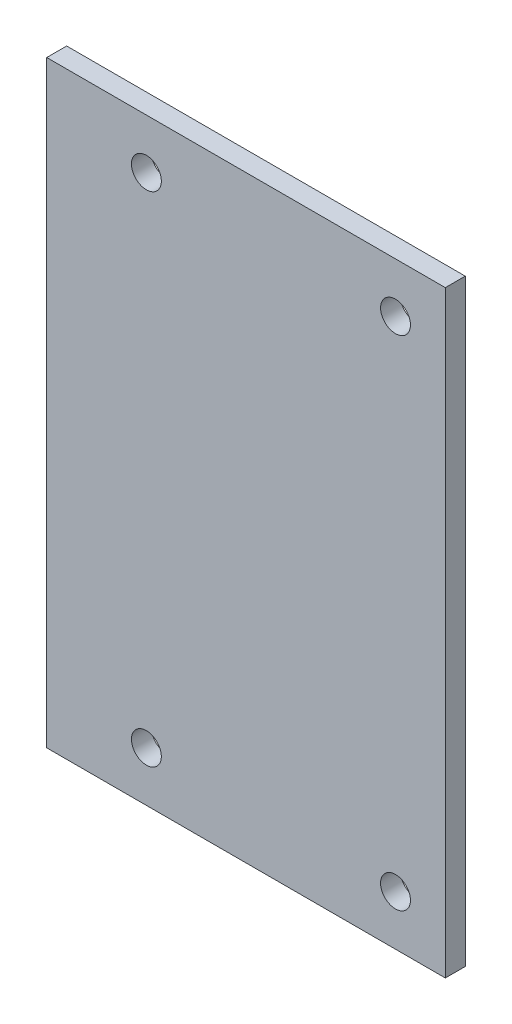
SolidWorks part; units mm, degrees
ref_plane "前视基准面" through (0, 0, 0) normal (0, 0, 1) x (1, 0, 0)
ref_plane "上视基准面" through (0, 0, 0) normal (0, 1, 0) x (1, 0, 0)
ref_plane "右视基准面" through (0, 0, 0) normal (1, 0, 0) x (0, 0, -1)
sketch "草图1" plane through (0, 0, 0) normal (0, 0, 1) x (1, 0, 0)
  line L0 (0, 30) -> (40, 30) construction
  line L1 (0, 0) -> (40, 0)
  line L2 (0, 0) -> (0, 60)
  line L3 (0, 60) -> (40, 60)
  line L4 (40, 0) -> (40, 60)
  line L5 (20, 60) -> (20, 0) construction
  circle A0 centre (10, 55) radius 1.5
  circle A1 centre (35, 55) radius 1.5
  circle A2 centre (10, 5) radius 1.5
  circle A3 centre (35, 5) radius 1.5
  dimension "D3" = 3
  dimension "D4" = 3
  dimension "D6" = 20
  dimension "D7" = 25
  dimension "D8" = 25
  dimension "D1" = 40
  dimension "D2" = 60
  dimension "D5" = 25
extrude "凸台-拉伸2" add sketch "草图1" along normal blind 2
